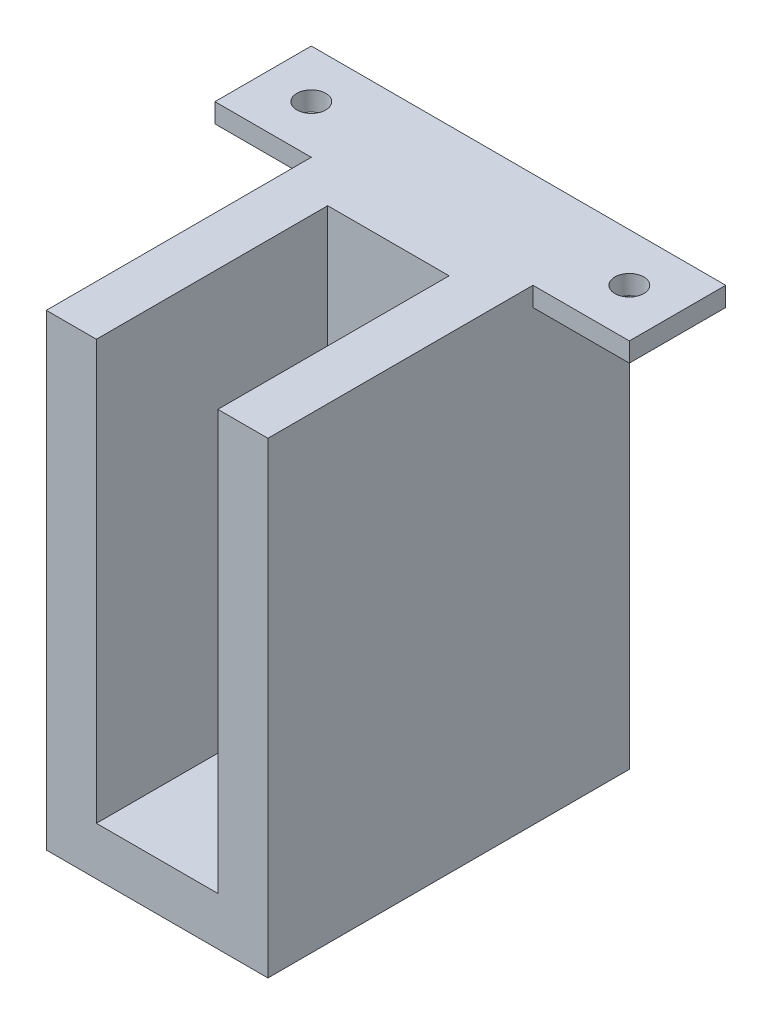
SolidWorks part; units mm, degrees
ref_plane "Front Plane" through (0, 0, 0) normal (0, 0, 1) x (1, 0, 0)
ref_plane "Top Plane" through (0, 0, 0) normal (0, 1, 0) x (1, 0, 0)
ref_plane "Right Plane" through (0, 0, 0) normal (1, 0, 0) x (0, 0, -1)
sketch "Sketch1" plane through (0, 0, 0) normal (0, 1, 0) x (1, 0, 0)
  line L1 (-11.5, -18.75) -> (11.5, -18.75)
  line L2 (-11.5, -18.75) -> (-11.5, 18.75)
  line L3 (-11.5, 18.75) -> (11.5, 18.75)
  line L4 (11.5, -18.75) -> (11.5, 18.75)
  line L5 (-11.5, -18.75) -> (11.5, 18.75) construction
  line L6 (-11.5, 18.75) -> (11.5, -18.75) construction
  point P0 (0, 0)
  dimension "D1" = 23
  dimension "D2" = 37.5
extrude "Boss-Extrude1" add sketch "Sketch1" along normal blind 48.5
sketch "Sketch2" plane through (0, 48.5, 0) normal (0, 1, 0) x (1, 0, 0)
  line L0 (-11.5, -18.75) -> (11.5, -18.75) construction
  line L1 (-6.3, -18.75) -> (6.3, -18.75)
  line L2 (-6.3, -18.75) -> (-6.3, 5.25)
  line L3 (-6.3, 5.25) -> (6.3, 5.25)
  line L4 (6.3, -18.75) -> (6.3, 5.25)
  line L5 (-11.5, 18.75) -> (-11.5, -18.75) construction
  dimension "D1" = 24
  dimension "D2" = 12.6
  dimension "D3" = 5.2
extrude "Cut-Extrude1" cut sketch "Sketch2" against normal blind 43.5
sketch "Sketch3" plane through (0, 0, -5.25) normal (0, 0, 1) x (1, 0, 0)
  line L0 (6.3, 5) -> (6.3, 48.5) construction
  line L1 (6.3, 25) -> (-6.3, 25)
  line L2 (6.3, 25) -> (6.3, 28)
  line L3 (6.3, 28) -> (-6.3, 28)
  line L4 (-6.3, 25) -> (-6.3, 28)
  line L5 (-6.3, 5) -> (-6.3, 48.5) construction
  line L6 (6.3, 5) -> (-6.3, 5) construction
  dimension "D1" = 20
  dimension "D2" = 3
extrude "Cut-Extrude2" cut sketch "Sketch3" against normal blind 5
sketch "Sketch4" plane through (-11.5, 0, 0) normal (-1, 0, 0) x (0, 0, 1)
  line L1 (-18.75, 48.5) -> (-8.75, 48.5)
  line L2 (-18.75, 48.5) -> (-18.75, 46.5)
  line L3 (-18.75, 46.5) -> (-8.75, 46.5)
  line L4 (-8.75, 48.5) -> (-8.75, 46.5)
  dimension "D1" = 2
  dimension "D2" = 10
extrude "Boss-Extrude2" add sketch "Sketch4" along normal blind 10
sketch "Sketch5" plane through (11.5, 0, 0) normal (1, 0, 0) x (0, 0, -1)
  line L1 (18.75, 48.5) -> (8.75, 48.5)
  line L2 (18.75, 48.5) -> (18.75, 46.5)
  line L3 (18.75, 46.5) -> (8.75, 46.5)
  line L4 (8.75, 48.5) -> (8.75, 46.5)
  dimension "D1" = 10
  dimension "D2" = 2
extrude "Boss-Extrude3" add sketch "Sketch5" along normal blind 10
sketch "Sketch6" plane through (0, 48.5, 0) normal (0, 1, 0) x (1, 0, 0)
  line L0 (21.5, 18.75) -> (-21.5, 18.75) construction
  line L1 (21.5, 18.75) -> (21.5, 8.75) construction
  line L2 (-21.5, 8.75) -> (-21.5, 18.75) construction
  line L3 (-21.5, 8.75) -> (-11.5, 8.75) construction
  circle A0 centre (16.5, 13.75) radius 1.5
  circle A1 centre (-16.5, 13.75) radius 1.5
  dimension "D1" = 3
  dimension "D4" = 3
  dimension "D2" = 5
  dimension "D3" = 5
  dimension "D5" = 5
  dimension "D6" = 5
extrude "Cut-Extrude3" cut sketch "Sketch6" against normal blind 10
